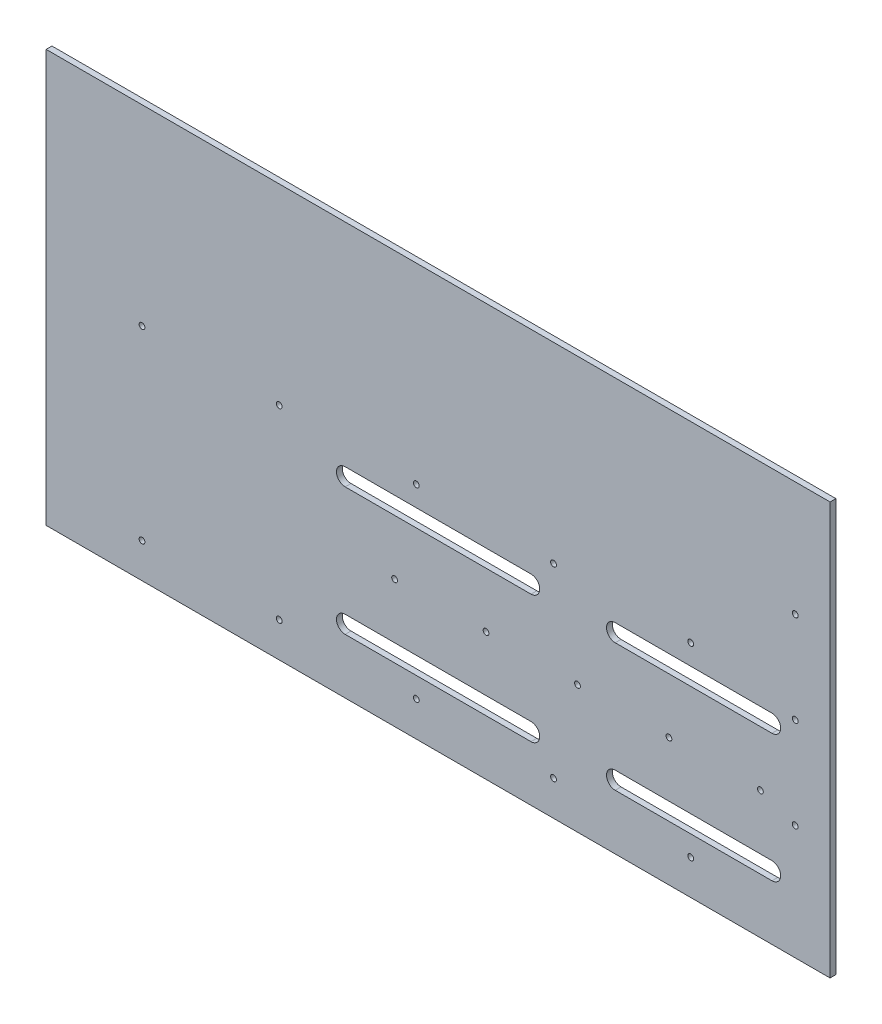
SolidWorks part; units mm, degrees
ref_plane "Front Plane" through (0, 0, 0) normal (0, 0, 1) x (1, 0, 0)
ref_plane "Top Plane" through (0, 0, 0) normal (0, 1, 0) x (1, 0, 0)
ref_plane "Right Plane" through (0, 0, 0) normal (1, 0, 0) x (0, 0, -1)
sketch "Sketch1" plane through (0, 0, 0) normal (0, 0, 1) x (1, 0, 0)
  line L1 (-428.625, 225.425) -> (428.625, 225.425)
  line L2 (-428.625, 225.425) -> (-428.625, -225.425)
  line L3 (-428.625, -225.425) -> (428.625, -225.425)
  line L4 (428.625, 225.425) -> (428.625, -225.425)
  point P4 (0, -225.425)
  point P6 (-428.625, 0)
  dimension "D1" = 857.25
  dimension "D2" = 450.85
extrude "Boss-Extrude1" add sketch "Sketch1" along normal blind 6.35
sketch "Sketch2" plane through (0, 0, 6.35) normal (0, 0, 1) x (1, 0, 0)
  line L0 (152.425, -85.725) -> (252.425, -85.725) construction
  line L1 (252.425, -85.725) -> (352.425, -85.725) construction
  line L2 (-47.575, -85.725) -> (52.425, -85.725) construction
  line L3 (52.425, -85.725) -> (152.425, -85.725) construction
  line L4 (-428.625, -225.425) -> (428.625, -225.425) construction
  line L5 (428.625, -225.425) -> (428.625, 225.425) construction
  line L6 (-101.6, -155.575) -> (101.6, -155.575) construction
  line L7 (-101.6, -146.05) -> (101.6, -146.05)
  line L8 (-101.6, -165.1) -> (101.6, -165.1)
  line L9 (193.675, -155.575) -> (365.125, -155.575) construction
  line L10 (193.675, -146.05) -> (365.125, -146.05)
  line L11 (193.675, -165.1) -> (365.125, -165.1)
  line L12 (-323.775, -187.325) -> (-173.775, -187.325) construction
  line L15 (365.125, -15.875) -> (193.675, -15.875) construction
  line L16 (365.125, -25.4) -> (193.675, -25.4)
  line L17 (365.125, -6.35) -> (193.675, -6.35)
  line L18 (-173.775, -187.325) -> (-23.775, -187.325) construction
  line L21 (101.6, -15.875) -> (-101.6, -15.875) construction
  line L22 (101.6, -25.4) -> (-101.6, -25.4)
  line L23 (101.6, -6.35) -> (-101.6, -6.35)
  line L24 (184.15, -155.575) -> (111.125, -155.575) construction
  line L25 (-23.775, -187.325) -> (126.225, -187.325) construction
  line L26 (126.225, -187.325) -> (276.225, -187.325) construction
  line L27 (-323.775, -187.325) -> (-428.625, -187.325) construction
  line L28 (-428.625, 225.425) -> (-428.625, -225.425) construction
  line L29 (276.225, -187.325) -> (428.625, -187.325) construction
  line L30 (-323.775, 15.875) -> (-173.775, 15.875) construction
  line L31 (-173.775, 15.875) -> (-23.775, 15.875) construction
  line L32 (-23.775, 15.875) -> (126.225, 15.875) construction
  line L33 (126.225, 15.875) -> (276.225, 15.875) construction
  circle A0 centre (352.425, -85.725) radius 3.175
  circle A1 centre (252.425, -85.725) radius 3.175
  circle A2 centre (152.425, -85.725) radius 3.175
  circle A3 centre (52.425, -85.725) radius 3.175
  circle A4 centre (-47.575, -85.725) radius 3.175
  arc A5 (-101.6, -146.05) -> (-101.6, -165.1) centre (-101.6, -155.575) ccw
  arc A6 (101.6, -165.1) -> (101.6, -146.05) centre (101.6, -155.575) ccw
  arc A7 (193.675, -146.05) -> (193.675, -165.1) centre (193.675, -155.575) ccw
  arc A8 (365.125, -165.1) -> (365.125, -146.05) centre (365.125, -155.575) ccw
  arc A11 (365.125, -25.4) -> (365.125, -6.35) centre (365.125, -15.875) ccw
  arc A12 (193.675, -6.35) -> (193.675, -25.4) centre (193.675, -15.875) ccw
  arc A15 (101.6, -25.4) -> (101.6, -6.35) centre (101.6, -15.875) ccw
  arc A16 (-101.6, -6.35) -> (-101.6, -25.4) centre (-101.6, -15.875) ccw
  circle A17 centre (276.225, -187.325) radius 3.175
  circle A18 centre (126.225, -187.325) radius 3.175
  circle A19 centre (-23.775, -187.325) radius 3.175
  circle A20 centre (-173.775, -187.325) radius 3.175
  circle A21 centre (-323.775, -187.325) radius 3.175
  circle A22 centre (276.225, 15.875) radius 3.175
  circle A23 centre (126.225, 15.875) radius 3.175
  circle A24 centre (-23.775, 15.875) radius 3.175
  circle A25 centre (-173.775, 15.875) radius 3.175
  circle A26 centre (-323.775, 15.875) radius 3.175
  point P16 (0, -155.575)
  point P23 (279.4, -155.575)
  point P28 (184.15, -155.575)
  point P29 (374.65, -155.575)
  point P42 (279.4, -15.875)
  point P54 (0, -15.875)
  point P67 (374.65, -15.875)
  point P71 (0, 0)
  dimension "D1" = 6.35
  dimension "D5" = 19.05
  dimension "D6" = 190.5
  dimension "D12" = 6.35
  dimension "D2" = 100
  dimension "D3" = 139.7
  dimension "D4" = 76.2
  dimension "D7" = 69.85
  dimension "D8" = 317.5
  dimension "D9" = 69.85
  dimension "D10" = 63.5
  dimension "D11" = 203.2
  dimension "D13" = 150
  dimension "D14" = 31.75
  dimension "D15" = 152.4
  dimension "D16" = 31.75
extrude "Cut-Extrude1" cut sketch "Sketch2" against normal through all
sketch "Sketch3" plane through (0, 0, 6.35) normal (0, 0, 1) x (1, 0, 0)
  line L0 (390.525, 0) -> (390.525, -100) construction
  line L1 (390.525, 100) -> (390.525, 0) construction
  line L2 (390.525, 100) -> (390.525, 225.425) construction
  line L3 (428.625, 225.425) -> (-428.625, 225.425) construction
  line L4 (390.525, -100) -> (390.525, -225.425) construction
  line L5 (-428.625, -225.425) -> (428.625, -225.425) construction
  line L6 (428.625, -225.425) -> (428.625, 225.425) construction
  circle A0 centre (390.525, -100) radius 3.175
  circle A1 centre (390.525, 0) radius 3.175
  circle A2 centre (390.525, 100) radius 3.175
  dimension "D1" = 6.35
  dimension "D2" = 100
  dimension "D3" = 38.1
extrude "Cut-Extrude2" cut sketch "Sketch3" against normal through all
